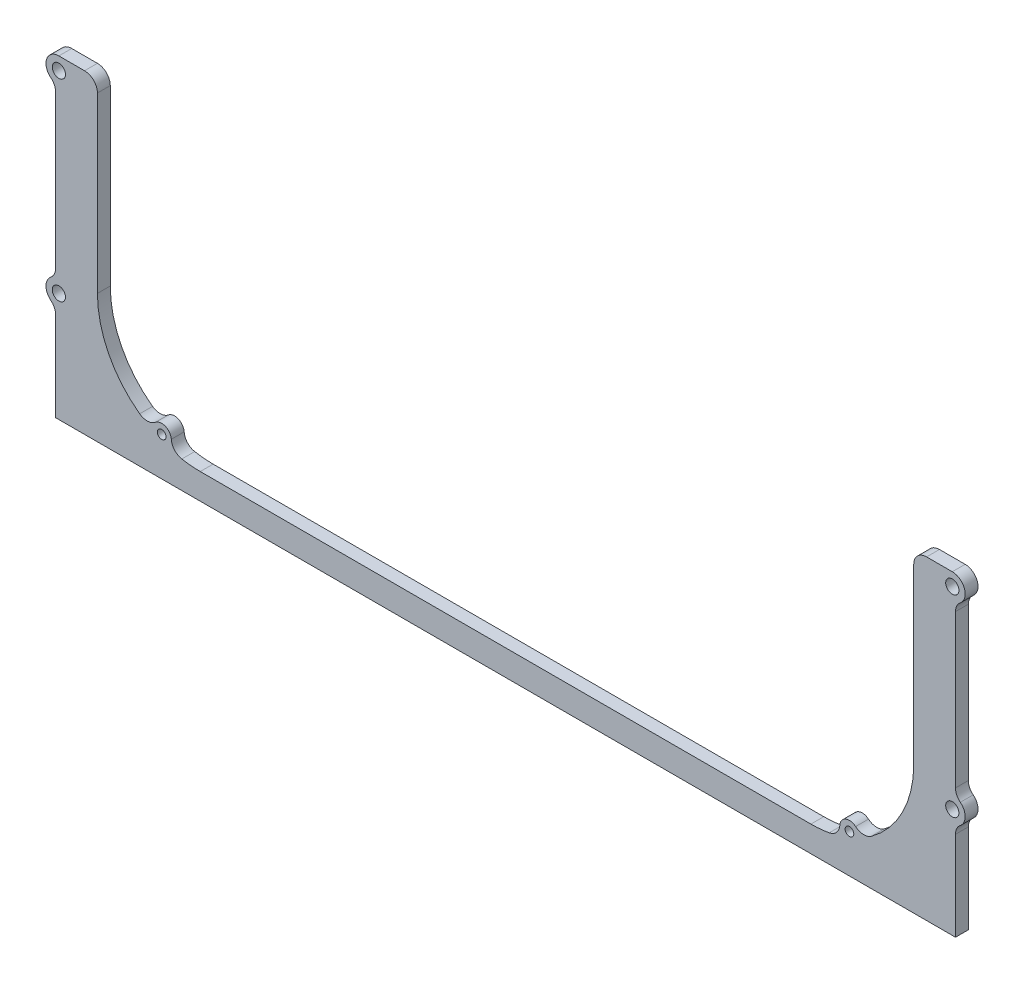
SolidWorks part; units mm, degrees
material "6061-T6 (SS)"
ref_plane "Front Plane" through (0, 0, 0) normal (0, 0, 1) x (1, 0, 0)
ref_plane "Top Plane" through (0, 0, 0) normal (0, 1, 0) x (1, 0, 0)
ref_plane "Right Plane" through (0, 0, 0) normal (1, 0, 0) x (0, 0, -1)
ref_plane "Plane1" through (0, 0, -190.5) normal (0, 0, -1) x (-1, 0, 0)
sketch "Sketch1" plane through (0, 0, -190.5) normal (0, 0, -1) x (-1, 0, 0)
  line L0 (-222.25, 187.1234) -> (-222.25, 270.0766)
  line L1 (-222.25, 304.8) -> (-222.25, 101.6) construction
  line L2 (-222.25, 174.8266) -> (-222.25, 127)
  line L3 (-220.6625, 282.575) -> (-201.6125, 282.575)
  line L4 (-201.6125, 282.575) -> (-201.6125, 190.5)
  line L5 (0, 127) -> (0, 210.2769) construction
  line L6 (0, 127) -> (-222.25, 127)
  line L7 (0, 127) -> (0, 139.7)
  line L8 (0, 139.7) -> (-150.8125, 139.7)
  line L9 (-169.8625, 114.3) -> (-169.8625, 146.05) construction
  line L10 (-188.9125, 114.3) -> (-150.8125, 114.3) construction
  circle A0 centre (-220.6625, 180.975) radius 3.2639
  circle A1 centre (-220.6625, 276.225) radius 3.2639
  circle A2 centre (-220.6625, 180.975) radius 6.35
  circle A3 centre (-220.6625, 276.225) radius 6.35
  arc A4 (-150.8125, 139.7) -> (-201.6125, 190.5) centre (-150.8125, 190.5) cw
  circle A5 centre (-169.8625, 146.05) radius 2.1463
  circle A6 centre (-169.8625, 146.05) radius 4.7625
  dimension "D1" = 6.5278
  dimension "D2" = 12.7
  dimension "D3" = 19.05
  dimension "D5" = 50.8
  dimension "D6" = 4.2926
  dimension "D7" = 31.75
  dimension "D8" = 9.525
  dimension "D4" = 12.7
extrude "Boss-Extrude1" add sketch "Sketch1" along normal blind 6.35 contours A6 A4 L4 L3 A3 L0 A2 L2 L6 L7 L8 | A3 A1 | A2 A0 | A4 A6 A5 | A4 A6
fillet "Fillet1" radius 6.35 2 edges at (174.6052, 145.6163, -193.675) (166.9057, 142.3165, -193.675)
fillet "Fillet2" radius 6.35 4 edges at (201.6125, 282.575, -193.675) (222.25, 270.0766, -193.675) (222.25, 187.1234, -193.675) (222.25, 174.8266, -193.675)
mirror "Mirror1" about plane through (0, 0, 0) normal (1, 0, 0) of "Fillet2", "Fillet1", "Boss-Extrude1"
